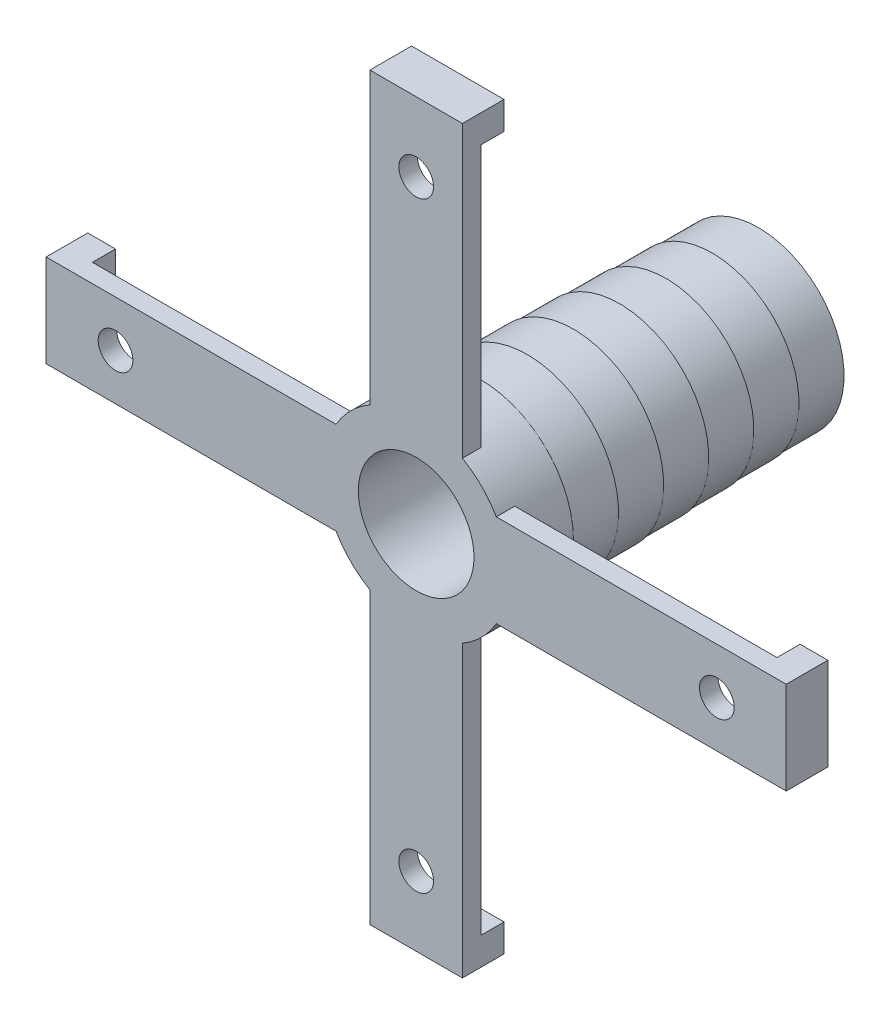
SolidWorks part; units mm, degrees
ref_plane "Front Plane" through (0, 0, 0) normal (0, 0, 1) x (1, 0, 0)
ref_plane "Top Plane" through (0, 0, 0) normal (0, 1, 0) x (1, 0, 0)
ref_plane "Right Plane" through (0, 0, 0) normal (1, 0, 0) x (0, 0, -1)
sketch "Sketch1" plane through (0, 0, 0) normal (0, 0, 1) x (1, 0, 0)
  circle A0 centre (0, 0) radius 10
  dimension "D1" = 20
extrude "Boss-Extrude1" add sketch "Sketch1" along normal blind 5
sketch "Sketch2" plane through (0, 0, 5) normal (0, 0, 1) x (1, 0, 0)
  line L1 (0, 5) -> (-40, 5)
  line L2 (0, 5) -> (0, -5)
  line L3 (0, -5) -> (-40, -5)
  line L4 (-40, 5) -> (-40, -5)
  line L5 (-5, 0) -> (5, 0)
  line L6 (-5, 0) -> (-5, 40)
  line L7 (-5, 40) -> (5, 40)
  line L8 (5, 0) -> (5, 40)
  line L9 (0, 5) -> (40, 5)
  line L10 (0, 5) -> (0, -5)
  line L11 (0, -5) -> (40, -5)
  line L12 (40, 5) -> (40, -5)
  line L13 (5, 0) -> (-5, 0)
  line L14 (5, 0) -> (5, -40)
  line L15 (5, -40) -> (-5, -40)
  line L16 (-5, 0) -> (-5, -40)
  point P5 (0, 0)
  point P18 (0, 0)
  point P19 (0, 0)
  point P20 (0, 0)
  circle M17 centre (0, 0) radius 10
  dimension "D1" = 40
  dimension "D2" = 10
extrude "Boss-Extrude2" add sketch "Sketch2" along normal blind 2 contours L1 L4 L3 M17 | L16 L6 L1 L3 M17 | L8 L7 L6 M17 | L1 L9 L8 L6 M17 | L12 L9 L11 M17 | L8 L14 L11 L9 M17 | L16 L15 L14 M17 | L3 L16 L14 L11 M17 | L14 L5 L2 L11 | L5 L16 L3 L2 | L9 L2 L5 L8 | L6 L5 L2 L1 | L1 L6 M17 | L8 L9 M17 | L11 L14 M17 | L16 L3 M17
sketch "Sketch3" plane through (0, 0, 0) normal (0, 0, -1) x (-1, 0, 0)
  circle A0 centre (0, 0) radius 9.875
  dimension "D1" = 19.75
extrude "Boss-Extrude3" add sketch "Sketch3" along normal blind 5
sketch "Sketch4" plane through (0, 0, -5) normal (0, 0, -1) x (-1, 0, 0)
  circle A0 centre (0, 0) radius 9.75
  dimension "D1" = 19.5
extrude "Boss-Extrude4" add sketch "Sketch4" along normal blind 5
sketch "Sketch5" plane through (0, 0, -10) normal (0, 0, -1) x (-1, 0, 0)
  circle A0 centre (0, 0) radius 9.625
  dimension "D1" = 19.25
extrude "Boss-Extrude5" add sketch "Sketch5" along normal blind 5
sketch "Sketch6" plane through (0, 0, -15) normal (0, 0, -1) x (-1, 0, 0)
  circle A0 centre (0, 0) radius 9.5
  dimension "D1" = 19
extrude "Boss-Extrude6" add sketch "Sketch6" along normal blind 5
sketch "Sketch7" plane through (0, 0, -20) normal (0, 0, -1) x (-1, 0, 0)
  circle A0 centre (0, 0) radius 9.375
  dimension "D1" = 18.75
extrude "Boss-Extrude7" add sketch "Sketch7" along normal blind 5
sketch "Sketch8" plane through (0, 0, -25) normal (0, 0, -1) x (-1, 0, 0)
  circle A0 centre (0, 0) radius 9.25
  dimension "D1" = 18.5
extrude "Boss-Extrude8" add sketch "Sketch8" along normal blind 5
sketch "Sketch9" plane through (0, 0, 5) normal (0, 0, -1) x (-1, 0, 0)
  line L1 (-40, 5) -> (-37, 5)
  line L2 (-40, 5) -> (-40, -5)
  line L3 (-40, -5) -> (-37, -5)
  line L4 (-37, 5) -> (-37, -5)
  line L5 (5, 40) -> (-5, 40)
  line L6 (5, 40) -> (5, 37)
  line L7 (5, 37) -> (-5, 37)
  line L8 (-5, 40) -> (-5, 37)
  line L9 (40, -5) -> (40, 5)
  line L10 (40, -5) -> (37, -5)
  line L11 (37, -5) -> (37, 5)
  line L12 (40, 5) -> (37, 5)
  line L13 (-5, -40) -> (5, -40)
  line L14 (-5, -40) -> (-5, -37)
  line L15 (-5, -37) -> (5, -37)
  line L16 (5, -40) -> (5, -37)
  point P22 (0, 0)
  dimension "D2" = 3
  dimension "D1" = 4
extrude "Boss-Extrude9" add sketch "Sketch9" along normal blind 2.5
sketch "Sketch10" plane through (0, 0, 5) normal (0, 0, -1) x (-1, 0, 0)
  line L0 (-32.5, 0) -> (32.5, 0) construction
  line L1 (0, 32.5) -> (0, -32.5) construction
  circle A0 centre (-32.5, 0) radius 1.875
  circle A1 centre (0, 32.5) radius 1.875
  circle A2 centre (32.5, 0) radius 1.875
  circle A3 centre (0, -32.5) radius 1.875
  point P8 (0, 0)
  point P9 (0, 0)
  dimension "D1" = 3.75
  dimension "D2" = 65
extrude "Cut-Extrude1" cut sketch "Sketch10" against normal through all both and the other way through all
sketch "Sketch11" plane through (0, 0, -30) normal (0, 0, -1) x (-1, 0, 0)
  circle A0 centre (0, 0) radius 6.25
  circle A1 centre (0, 0) radius 9.25 construction
  dimension "D1" = 3
extrude "Cut-Extrude2" cut sketch "Sketch11" against normal through all both and the other way through all
